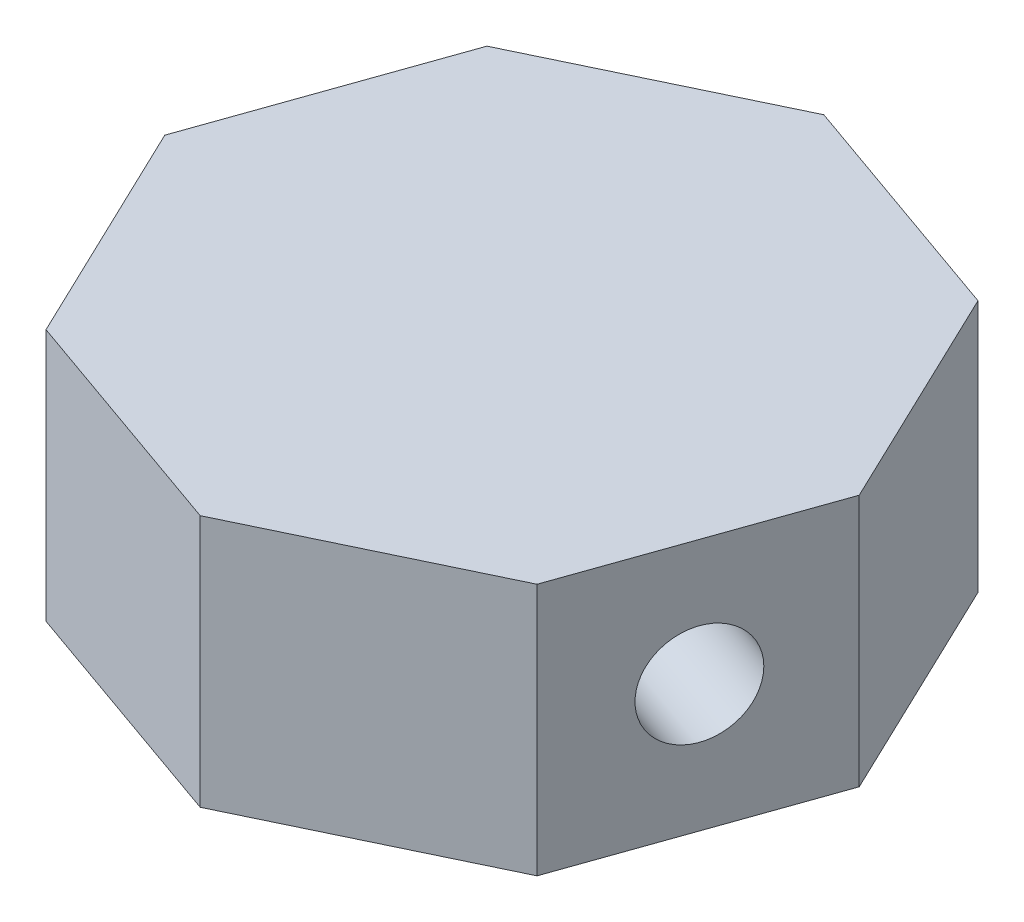
SolidWorks part; units mm, degrees
ref_plane "Front Plane" through (0, 0, 0) normal (0, 0, 1) x (1, 0, 0)
ref_plane "Top Plane" through (0, 0, 0) normal (0, 1, 0) x (1, 0, 0)
ref_plane "Right Plane" through (0, 0, 0) normal (1, 0, 0) x (0, 0, -1)
sketch "Sketch1" plane through (0, 0, 0) normal (0, 1, 0) x (1, 0, 0)
  line L1 (78.512, -146.1841) -> (158.8841, -47.8514)
  line L2 (158.8841, -47.8514) -> (146.1841, 78.512)
  line L3 (146.1841, 78.512) -> (47.8514, 158.8841)
  line L4 (47.8514, 158.8841) -> (-78.512, 146.1841)
  line L5 (-78.512, 146.1841) -> (-158.8841, 47.8514)
  line L6 (-158.8841, 47.8514) -> (-146.1841, -78.512)
  line L7 (-146.1841, -78.512) -> (-47.8514, -158.8841)
  line L9 (-47.8514, -158.8841) -> (78.512, -146.1841) [skipped]
  line L10 (4.8364, 12.0753) -> (-0.6466, 23.5308)
  line L11 (-0.6466, 23.5308) -> (-12.6238, 27.7539)
  line L12 (-12.6238, 27.7539) -> (-24.0793, 22.271)
  line L13 (-24.0793, 22.271) -> (-28.3024, 10.2937)
  line L14 (-28.3024, 10.2937) -> (-22.8195, -1.1617)
  line L15 (-22.8195, -1.1617) -> (-10.8422, -5.3849)
  line L16 (-10.8422, -5.3849) -> (0.6132, 0.0981)
  line L17 (0.6132, 0.0981) -> (4.8364, 12.0753)
  circle A0 centre (0, 0) radius 153.3026 construction
  circle A1 centre (-11.733, 11.1845) radius 15.3303 construction
  dimension "D1" = 12.7
  dimension "D2" = 12.7
extrude "Boss-Extrude1" add sketch "Sketch1" along normal blind 12.7 contours L16 L17 L10 L11 L12 L13 L14 L15
sketch "Sketch2" plane through (0.5147, 0, 0.1815) normal (0.9431, 0, 0.3325) x (0.3325, 0, -0.9431)
  line L0 (12.9964, 12.7) -> (0.2964, 0)
  line L1 (0.2964, 0) -> (12.9964, 0)
  line L2 (12.9964, 0) -> (0.2964, 12.7)
  circle A0 centre (6.6964, 6.4) radius 2.54
extrude "Cut-Extrude1" cut sketch "Sketch2" against normal blind 12.7 contours L2 A0 L0 | L0 A0 L2 | L2 A0 L0 | L0 A0 L2
sketch "Sketch3" plane through (0, 0, 0) normal (0, -1, 0) x (1, 0, 0)
  line L0 (-0.6466, -23.5308) -> (-22.918, 1.2089)
  line L1 (-22.918, 1.2089) -> (-28.3024, -10.2937)
  line L2 (-28.3024, -10.2937) -> (4.8364, -12.0753)
  circle A0 centre (-11.7823, -11.1609) radius 3.175
extrude "Cut-Extrude2" cut sketch "Sketch3" against normal blind 2.54 contours L2 A0 L0 | L0 A0 L2 | L2 A0 L0 | L0 A0 L2
